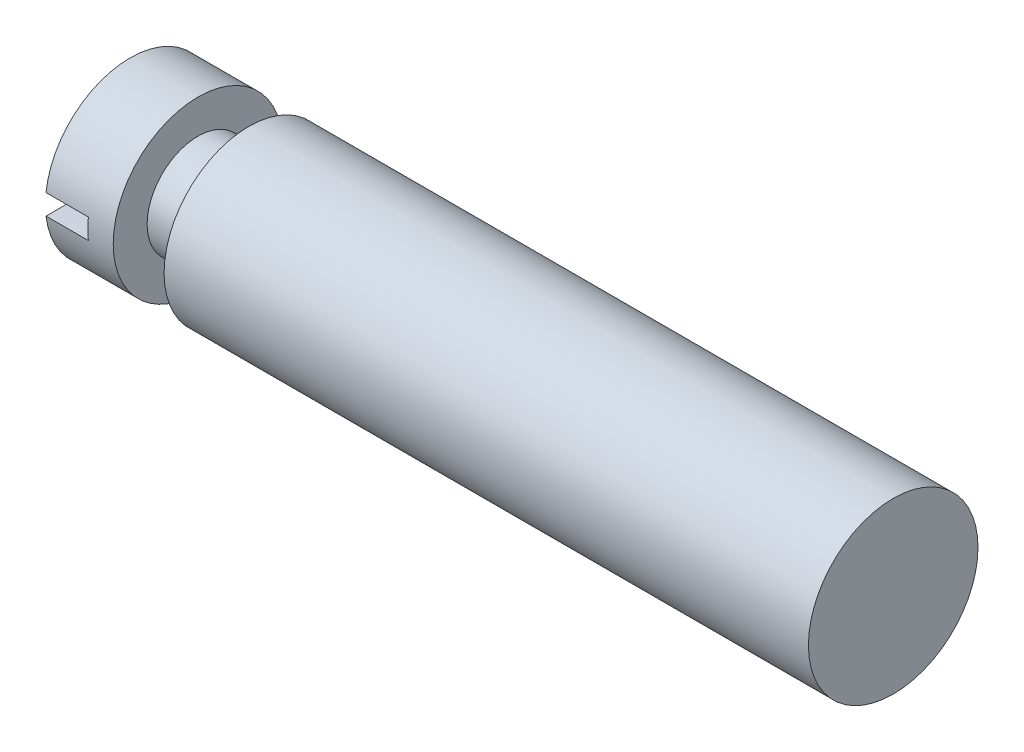
SolidWorks part; units mm, degrees
ref_plane "Front Plane" through (0, 0, 0) normal (0, 0, 1) x (1, 0, 0)
ref_plane "Top Plane" through (0, 0, 0) normal (0, 1, 0) x (1, 0, 0)
ref_plane "Right Plane" through (0, 0, 0) normal (1, 0, 0) x (0, 0, -1)
sketch "Sketch1" plane through (0, 0, 0) normal (0, 0, 1) x (1, 0, 0)
  line L0 (0, 0) -> (45, 0) construction
  line L1 (4, 5) -> (4, 3)
  line L2 (0, 0) -> (45, 0)
  line L3 (0, 0) -> (0, 5)
  line L4 (0, 5) -> (4, 5)
  line L5 (45, 0) -> (45, 5)
  line L6 (4, 3) -> (7, 3)
  line L7 (7, 3) -> (7, 5)
  line L8 (7, 5) -> (45, 5)
  dimension "D" = 10
  dimension "L" = 45
  dimension "F" = 4
  dimension "A" = 3
  dimension "D_s" = 6
revolve "Revolve1" add sketch "Sketch1" angle 360 about L0
cosmetic thread "Cosmetic Thread1" [suppressed]
cosmetic thread "Cosmetic Thread2"
sketch "Sketch2" plane through (0, 0, 0) normal (0, 0, 1) x (1, 0, 0)
  line L0 (0, 0) -> (2.5, 0) construction
  line L2 (0, -0.6) -> (2.5, -0.6)
  line L3 (0, -0.6) -> (0, 0.6)
  line L4 (0, 0.6) -> (2.5, 0.6)
  line L5 (2.5, -0.6) -> (2.5, 0.6)
  dimension "T" = 1.2
  dimension "H" = 2.5
extrude "Cut-Extrude1" cut sketch "Sketch2" against normal through all and the other way through all
